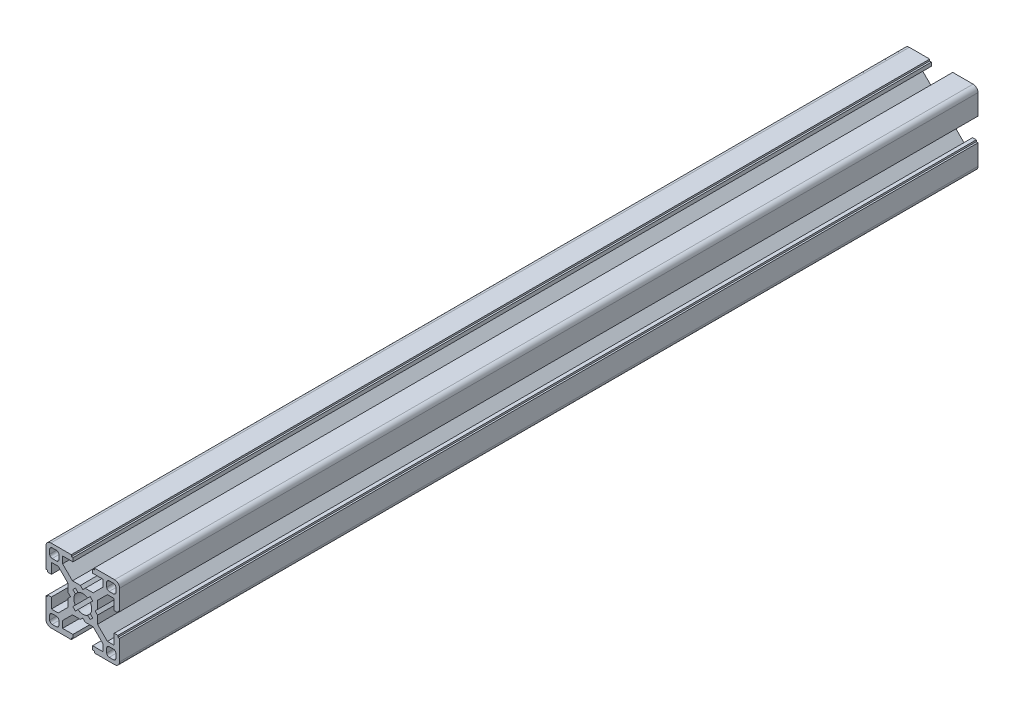
SolidWorks part; units mm, degrees
material "6063-O, Barra estrusa (SS)"
ref_plane "Piano frontale" through (0, 0, 0) normal (0, 0, 1) x (1, 0, 0)
ref_plane "Piano superiore" through (0, 0, 0) normal (0, 1, 0) x (1, 0, 0)
ref_plane "Piano destro" through (0, 0, 0) normal (1, 0, 0) x (0, 0, -1)
sketch "Schizzo1" plane through (0, 0, 0) normal (0, 0, 1) x (1, 0, 0)
  line L0 (-125.0647, 0) -> (53.776, 0) construction
  line L1 (0, -44.8297) -> (0, 95.2781) construction
  line L2 (-15, 13) -> (-15, 4.7)
  line L3 (-15, 4.7) -> (-14.3, 4.7)
  line L4 (-14.3, 4.7) -> (-14.3, 4)
  line L5 (-14.3, 4) -> (-12.8, 4)
  line L6 (-12.8, 4) -> (-12.8, 8.25)
  line L7 (-12.8, 8.25) -> (-10.0178, 8.25)
  line L8 (-10.0178, 8.25) -> (-6, 4.2322)
  line L9 (-6, 4.2322) -> (-6, 1)
  line L10 (-6, 1) -> (-5, 0)
  line L11 (-1, 6) -> (0, 5)
  line L12 (0, 0) -> (-161.3113, 161.3113) construction
  line L13 (-4.2322, 6) -> (-1, 6)
  line L14 (-8.25, 10.0178) -> (-4.2322, 6)
  line L15 (-8.25, 12.8) -> (-8.25, 10.0178)
  line L16 (-4, 12.8) -> (-8.25, 12.8)
  line L17 (-4, 14.3) -> (-4, 12.8)
  line L18 (-4.7, 14.3) -> (-4, 14.3)
  line L19 (-4.7, 15) -> (-4.7, 14.3)
  line L20 (-13, 15) -> (-4.7, 15)
  line L21 (13.5, 10.75) -> (13.5, 12.5)
  line L22 (10.75, 13.5) -> (12.5, 13.5)
  line L23 (9.75, 10.75) -> (9.75, 12.5)
  line L24 (10.75, 9.75) -> (12.5, 9.75)
  line L25 (10.75, -13.5) -> (12.5, -13.5)
  line L26 (13.5, -10.75) -> (13.5, -12.5)
  line L27 (10.75, -9.75) -> (12.5, -9.75)
  line L28 (9.75, -10.75) -> (9.75, -12.5)
  line L29 (-13.5, -10.75) -> (-13.5, -12.5)
  line L30 (-10.75, -13.5) -> (-12.5, -13.5)
  line L31 (-9.75, -10.75) -> (-9.75, -12.5)
  line L32 (-10.75, -9.75) -> (-12.5, -9.75)
  line L33 (1.9955, 3.0562) -> (3.0052, 4.0659)
  line L34 (3.0052, 4.0659) -> (4.0659, 3.0052)
  line L35 (4.0659, 3.0052) -> (3.0562, 1.9955)
  line L36 (3.0562, -1.9955) -> (4.0659, -3.0052)
  line L37 (4.0659, -3.0052) -> (3.0052, -4.0659)
  line L38 (3.0052, -4.0659) -> (1.9955, -3.0562)
  line L39 (-1.9955, -3.0562) -> (-3.0052, -4.0659)
  line L40 (-3.0052, -4.0659) -> (-4.0659, -3.0052)
  line L41 (-4.0659, -3.0052) -> (-3.0562, -1.9955)
  line L42 (1, 6) -> (0, 5)
  line L43 (4.2322, 6) -> (1, 6)
  line L44 (8.25, 10.0178) -> (4.2322, 6)
  line L45 (8.25, 12.8) -> (8.25, 10.0178)
  line L46 (4, 12.8) -> (8.25, 12.8)
  line L47 (12.8, 4) -> (12.8, 8.25)
  line L48 (12.8, 8.25) -> (10.0178, 8.25)
  line L49 (10.0178, 8.25) -> (6, 4.2322)
  line L50 (6, 4.2322) -> (6, 1)
  line L51 (6, 1) -> (5, 0)
  line L52 (6, -1) -> (5, 0)
  line L53 (6, -4.2322) -> (6, -1)
  line L54 (10.0178, -8.25) -> (6, -4.2322)
  line L55 (12.8, -8.25) -> (10.0178, -8.25)
  line L56 (12.8, -4) -> (12.8, -8.25)
  line L57 (4, -12.8) -> (8.25, -12.8)
  line L58 (8.25, -12.8) -> (8.25, -10.0178)
  line L59 (8.25, -10.0178) -> (4.2322, -6)
  line L60 (4.2322, -6) -> (1, -6)
  line L61 (1, -6) -> (0, -5)
  line L62 (-1, -6) -> (0, -5)
  line L63 (-4.2322, -6) -> (-1, -6)
  line L64 (-8.25, -10.0178) -> (-4.2322, -6)
  line L65 (-8.25, -12.8) -> (-8.25, -10.0178)
  line L66 (-4, -12.8) -> (-8.25, -12.8)
  line L67 (-12.8, -4) -> (-12.8, -8.25)
  line L68 (-12.8, -8.25) -> (-10.0178, -8.25)
  line L69 (-10.0178, -8.25) -> (-6, -4.2322)
  line L70 (-6, -4.2322) -> (-6, -1)
  line L71 (-6, -1) -> (-5, 0)
  line L72 (4, 14.3) -> (4, 12.8)
  line L73 (4.7, 14.3) -> (4, 14.3)
  line L74 (4.7, 15) -> (4.7, 14.3)
  line L75 (-3.0562, 1.9955) -> (-4.0659, 3.0052)
  line L76 (-4.0659, 3.0052) -> (-3.0052, 4.0659)
  line L77 (-3.0052, 4.0659) -> (-1.9955, 3.0562)
  line L78 (15, 4.7) -> (14.3, 4.7)
  line L79 (-10.75, 9.75) -> (-12.5, 9.75)
  line L80 (-9.75, 10.75) -> (-9.75, 12.5)
  line L81 (-10.75, 13.5) -> (-12.5, 13.5)
  line L82 (-13.5, 10.75) -> (-13.5, 12.5)
  line L83 (14.3, 4.7) -> (14.3, 4)
  line L84 (14.3, 4) -> (12.8, 4)
  line L85 (14.3, -4) -> (12.8, -4)
  line L86 (14.3, -4.7) -> (14.3, -4)
  line L87 (15, -4.7) -> (14.3, -4.7)
  line L88 (4.7, -15) -> (4.7, -14.3)
  line L89 (4.7, -14.3) -> (4, -14.3)
  line L90 (4, -14.3) -> (4, -12.8)
  line L91 (-4, -14.3) -> (-4, -12.8)
  line L92 (-4.7, -14.3) -> (-4, -14.3)
  line L93 (-4.7, -15) -> (-4.7, -14.3)
  line L94 (-15, -4.7) -> (-14.3, -4.7)
  line L95 (-14.3, -4.7) -> (-14.3, -4)
  line L96 (-14.3, -4) -> (-12.8, -4)
  line L97 (4, 14.3) -> (4, 12.8)
  line L98 (4.7, 14.3) -> (4, 14.3)
  line L99 (4.7, 15) -> (4.7, 14.3)
  line L100 (15, 4.7) -> (14.3, 4.7)
  line L101 (14.3, 4.7) -> (14.3, 4)
  line L102 (14.3, 4) -> (12.8, 4)
  line L103 (13, 15) -> (4.7, 15)
  line L104 (15, 13) -> (15, 4.7)
  line L105 (14.3, -4) -> (12.8, -4)
  line L106 (14.3, -4.7) -> (14.3, -4)
  line L107 (15, -4.7) -> (14.3, -4.7)
  line L108 (4.7, -15) -> (4.7, -14.3)
  line L109 (4.7, -14.3) -> (4, -14.3)
  line L110 (4, -14.3) -> (4, -12.8)
  line L111 (15, -13) -> (15, -4.7)
  line L112 (13, -15) -> (4.7, -15)
  line L113 (-4, -14.3) -> (-4, -12.8)
  line L114 (-4.7, -14.3) -> (-4, -14.3)
  line L115 (-4.7, -15) -> (-4.7, -14.3)
  line L116 (-15, -4.7) -> (-14.3, -4.7)
  line L117 (-14.3, -4.7) -> (-14.3, -4)
  line L118 (-14.3, -4) -> (-12.8, -4)
  line L119 (-13, -15) -> (-4.7, -15)
  line L120 (-15, -13) -> (-15, -4.7)
  arc A0 (-3.65, 0) -> (-3.0562, 1.9955) centre (0, 0) cw
  arc A1 (-1.9955, 3.0562) -> (0, 3.65) centre (0, 0) cw
  arc A2 (-13, 15) -> (-15, 13) centre (-13, 13) ccw
  arc A3 (-13.5, 10.75) -> (-12.5, 9.75) centre (-12.5, 10.75) ccw
  arc A4 (-9.75, 10.75) -> (-10.75, 9.75) centre (-10.75, 10.75) cw
  arc A5 (-10.75, 13.5) -> (-9.75, 12.5) centre (-10.75, 12.5) cw
  arc A6 (-12.5, 13.5) -> (-13.5, 12.5) centre (-12.5, 12.5) ccw
  arc A7 (13.5, 12.5) -> (12.5, 13.5) centre (12.5, 12.5) ccw
  arc A8 (13.5, 10.75) -> (12.5, 9.75) centre (12.5, 10.75) cw
  arc A9 (10.75, 9.75) -> (9.75, 10.75) centre (10.75, 10.75) cw
  arc A10 (10.75, 13.5) -> (9.75, 12.5) centre (10.75, 12.5) ccw
  arc A11 (12.5, -13.5) -> (13.5, -12.5) centre (12.5, -12.5) ccw
  arc A12 (10.75, -13.5) -> (9.75, -12.5) centre (10.75, -12.5) cw
  arc A13 (9.75, -10.75) -> (10.75, -9.75) centre (10.75, -10.75) cw
  arc A14 (13.5, -10.75) -> (12.5, -9.75) centre (12.5, -10.75) ccw
  arc A15 (-13.5, -12.5) -> (-12.5, -13.5) centre (-12.5, -12.5) ccw
  arc A16 (-13.5, -10.75) -> (-12.5, -9.75) centre (-12.5, -10.75) cw
  arc A17 (-10.75, -9.75) -> (-9.75, -10.75) centre (-10.75, -10.75) cw
  arc A18 (-10.75, -13.5) -> (-9.75, -12.5) centre (-10.75, -12.5) ccw
  arc A19 (0, 3.65) -> (1.9955, 3.0562) centre (0, 0) cw
  arc A20 (3.0562, 1.9955) -> (3.65, 0) centre (0, 0) cw
  arc A21 (3.65, 0) -> (3.0562, -1.9955) centre (0, 0) cw
  arc A22 (1.9955, -3.0562) -> (0, -3.65) centre (0, 0) cw
  arc A23 (0, -3.65) -> (-1.9955, -3.0562) centre (0, 0) cw
  arc A24 (-3.0562, -1.9955) -> (-3.65, 0) centre (0, 0) cw
  arc A25 (15, 13) -> (13, 15) centre (13, 13) ccw
  arc A26 (13, -15) -> (15, -13) centre (13, -13) ccw
  arc A27 (-15, -13) -> (-13, -15) centre (-13, -13) ccw
  point P70 (0, 0)
  point P86 (0, 0)
  point P88 (-15, 15)
  point P100 (-9.75, 9.75)
  point P107 (0, 0)
  point P144 (0, 0)
  point P169 (0, 0)
  point P197 (0, 0)
  dimension "D11" = 7.3
  dimension "D14" = 2
  dimension "D17" = 1
  dimension "D1" = 45
  dimension "D2" = 8
  dimension "D3" = 16.5
  dimension "D4" = 9
  dimension "D5" = 2.2
  dimension "D6" = 15
  dimension "D7" = 2.5
  dimension "D8" = 8.3
  dimension "D9" = 2
  dimension "D12" = 5
  dimension "D13" = 1.5
  dimension "D15" = 1.5
  dimension "D16" = 1.5
  dimension "D10" = 4
  dimension "D18" = 4
  dimension "D19" = 4
  dimension "D20" = 4
  dimension "D21" = 4
extrude "Estrusione-Estrusione2" add sketch "Schizzo1" along normal blind 350 contours L120 A27 L119 L93 L92 L91 L66 L65 L64 L63 L62 L61 L60 L59 L58 L57 L90 L89 L88 L112 A26 L111 L87 L86 L85 L56 L55 L54 L53 L52 L51 L50 L49 L48 L47 L84 L83 L78 L104 A25 L103 L74 L73 L72 L46 L45 L44 L43 L42 L11 L13
